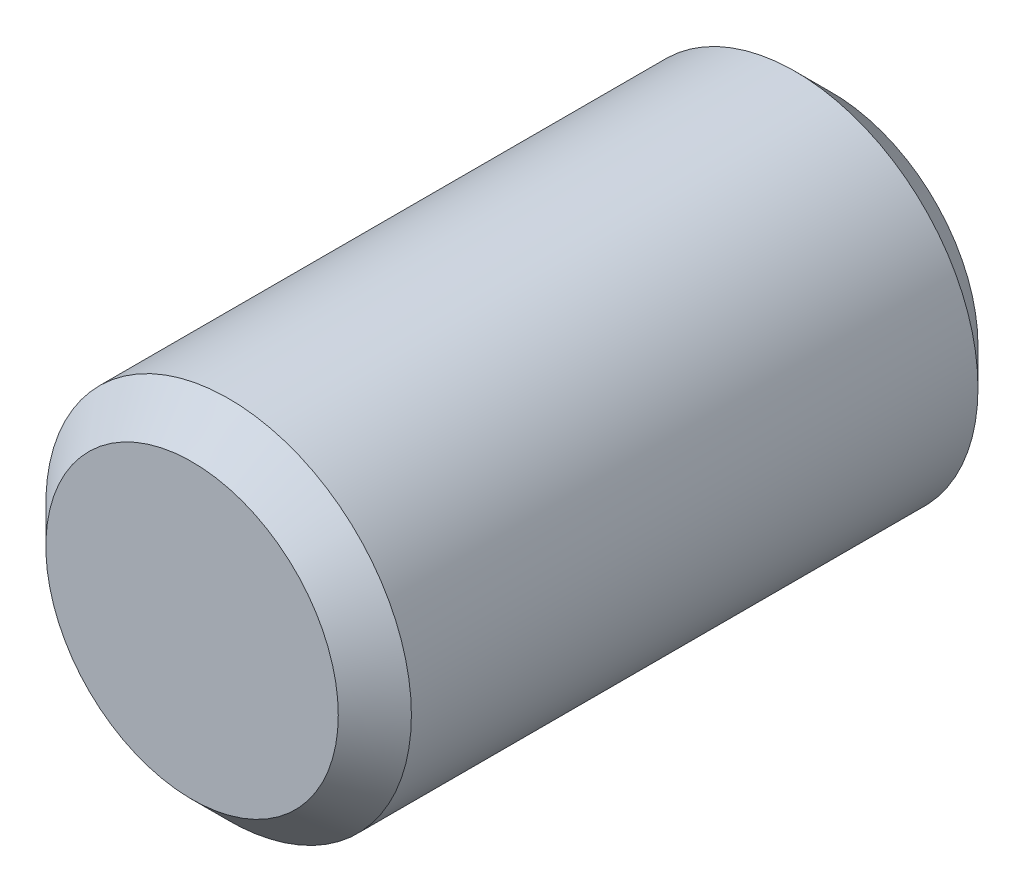
SolidWorks part; units mm, degrees
ref_plane "Front Plane" through (0, 0, 0) normal (0, 0, 1) x (1, 0, 0)
ref_plane "Top Plane" through (0, 0, 0) normal (0, 1, 0) x (1, 0, 0)
ref_plane "Right Plane" through (0, 0, 0) normal (1, 0, 0) x (0, 0, -1)
sketch "Sketch1" plane through (0, 0, 0) normal (0, 0, 1) x (1, 0, 0)
  circle A0 centre (0, 0) radius 5
  dimension "D1" = 10
extrude "Boss-Extrude1" add sketch "Sketch1" along normal mid plane 17.5
chamfer "Chamfer1" distance 1 angle 45 2 edges at (5, 0, -8.75) (5, 0, 8.75)
